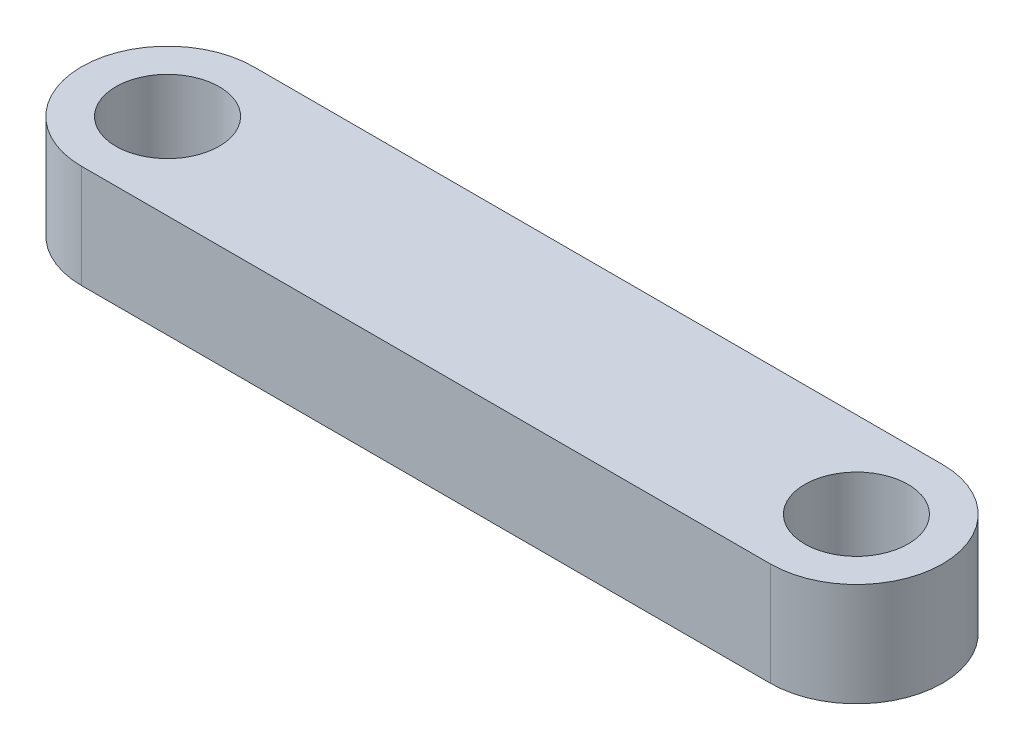
SolidWorks part; units mm, degrees
ref_plane "Alzado" through (0, 0, 0) normal (0, 0, 1) x (1, 0, 0)
ref_plane "Planta" through (0, 0, 0) normal (0, 1, 0) x (1, 0, 0)
ref_plane "Vista lateral" through (0, 0, 0) normal (1, 0, 0) x (0, 0, -1)
sketch "Croquis1" plane through (0, 0, 0) normal (0, 1, 0) x (1, 0, 0)
  line L0 (10, 0) -> (-10, 0) construction
  line L1 (10, -2.5) -> (-10, -2.5)
  line L2 (10, 2.5) -> (-10, 2.5)
  arc A0 (10, -2.5) -> (10, 2.5) centre (10, 0) ccw
  arc A1 (-10, 2.5) -> (-10, -2.5) centre (-10, 0) ccw
  circle A2 centre (-10, 0) radius 1.5
  circle A3 centre (10, 0) radius 1.5
  point P2 (0, 0)
  dimension "D2" = 2.5
  dimension "D3" = 3
  dimension "D4" = 3
  dimension "D1" = 20
extrude "Saliente-Extruir1" add sketch "Croquis1" along normal mid plane 3
